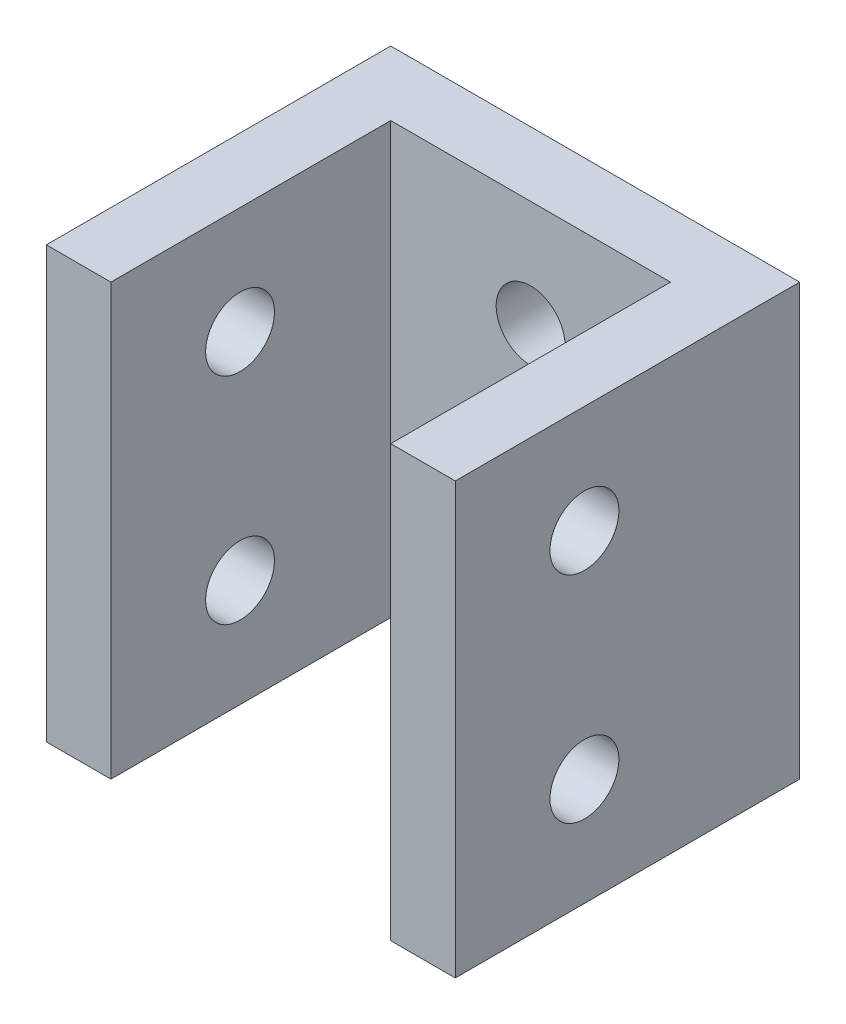
SolidWorks part; units mm, degrees
ref_plane "前视基准面" through (0, 0, 0) normal (0, 0, 1) x (1, 0, 0)
ref_plane "上视基准面" through (0, 0, 0) normal (0, 1, 0) x (1, 0, 0)
ref_plane "右视基准面" through (0, 0, 0) normal (1, 0, 0) x (0, 0, -1)
sketch "草图1" plane through (0, 0, 0) normal (0, 0, 1) x (1, 0, 0)
  line L1 (253.9883, -63.1089) -> (272.9883, -63.1089)
  line L2 (253.9883, -63.1089) -> (253.9883, -43.1089)
  line L3 (253.9883, -43.1089) -> (272.9883, -43.1089)
  line L4 (272.9883, -63.1089) -> (272.9883, -43.1089)
  dimension "D1" = 19
  dimension "D2" = 20
extrude "凸台-拉伸1" add sketch "草图1" along normal blind 3
sketch "草图2" plane through (0, 0, 3) normal (0, 0, 1) x (1, 0, 0)
  line L0 (253.9883, -43.1089) -> (253.9883, -63.1089) construction
  line L1 (253.9883, -63.1089) -> (256.9883, -63.1089)
  line L2 (253.9883, -63.1089) -> (253.9883, -43.1089)
  line L3 (253.9883, -43.1089) -> (256.9883, -43.1089)
  line L4 (256.9883, -63.1089) -> (256.9883, -43.1089)
  line L5 (272.9883, -43.1089) -> (253.9883, -43.1089) construction
  line L6 (253.9883, -63.1089) -> (272.9883, -63.1089) construction
  line L7 (272.9883, -43.1089) -> (269.9883, -43.1089)
  line L8 (272.9883, -43.1089) -> (272.9883, -63.1089)
  line L9 (272.9883, -63.1089) -> (269.9883, -63.1089)
  line L10 (269.9883, -43.1089) -> (269.9883, -63.1089)
  dimension "D1" = 3
  dimension "D2" = 3
extrude "凸台-拉伸2" add sketch "草图2" along normal blind 15
sketch "草图3" plane through (253.9883, 0, 0) normal (-1, 0, 0) x (0, 0, 1)
  line L0 (18, -63.1089) -> (0, -63.1089) construction
  line L1 (18, -43.1089) -> (18, -63.1089) construction
  circle A0 centre (10, -48.1089) radius 1.6
  circle A1 centre (10, -58.1089) radius 1.6
  dimension "D1" = 3.2
  dimension "D2" = 3.2
  dimension "D3" = 10
  dimension "D4" = 5
  dimension "D5" = 8
  dimension "D6" = 8
extrude "切除-拉伸1" cut sketch "草图3" against normal blind 30
sketch "草图4" plane through (0, 0, 3) normal (0, 0, 1) x (1, 0, 0)
  line L1 (256.9883, -63.1089) -> (269.9883, -63.1089) construction
  line L2 (269.9883, -43.1089) -> (269.9883, -63.1089) construction
  circle A0 centre (263.4883, -48.1089) radius 1.6
  circle A1 centre (263.4883, -58.1089) radius 1.6
  dimension "D1" = 3.2
  dimension "D2" = 3.2
  dimension "D4" = 5
  dimension "D6" = 6.5
  dimension "D3" = 10
  dimension "D5" = 6.5
extrude "切除-拉伸2" cut sketch "草图4" against normal blind 30
sketch "草图5" plane through (253.9883, 0, 0) normal (-1, 0, 0) x (0, 0, 1)
  line L0 (18, -43.1089) -> (0, -43.1089) construction
  line L1 (16, -43.1089) -> (25.9736, -43.1089)
  line L2 (16, -43.1089) -> (16, -68.5764)
  line L3 (16, -68.5764) -> (25.9736, -68.5764)
  line L4 (25.9736, -43.1089) -> (25.9736, -68.5764)
  line L5 (16, 18.8911) -> (16, -235.1089) construction
extrude "切除-拉伸3" cut sketch "草图5" against normal blind 29
